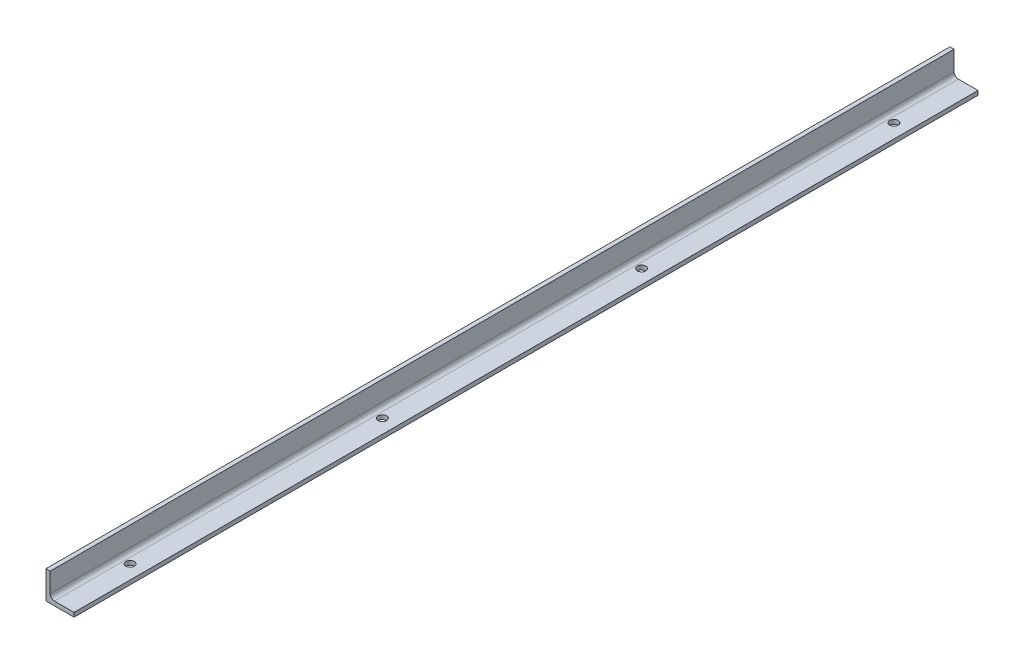
SolidWorks part; units mm, degrees
ref_plane "Plan de face" through (0, 0, 0) normal (0, 0, 1) x (1, 0, 0)
ref_plane "Plan de dessus" through (0, 0, 0) normal (0, 1, 0) x (1, 0, 0)
ref_plane "Plan de droite" through (0, 0, 0) normal (1, 0, 0) x (0, 0, -1)
sketch "Esquisse1" plane through (0, 0, 0) normal (0, 0, 1) x (1, 0, 0)
  line L0 (0, 0) -> (0, 20)
  line L1 (0, 20) -> (3, 20)
  line L2 (3, 20) -> (3, 6)
  line L3 (6, 3) -> (20, 3)
  line L4 (20, 3) -> (20, 0)
  line L5 (20, 0) -> (0, 0)
  arc A0 (3, 6) -> (6, 3) centre (6, 6) ccw
  dimension "D5" = 3
  dimension "D1" = 20
  dimension "D2" = 20
  dimension "D3" = 3
  dimension "D4" = 3
extrude "Boss.-Extru.1" add sketch "Esquisse1" along normal blind 645
sketch "Esquisse2" plane through (0, 0, 0) normal (0, -1, 0) x (-1, 0, 0)
  line L0 (0, 0) -> (-20, 0) construction
  line L1 (0, -645) -> (-20, -645) construction
  line L4 (0, -645) -> (0, 0) construction
  circle A0 centre (-10, -50) radius 3
  circle A1 centre (-10, -595) radius 3
  circle A2 centre (-10, -230) radius 3
  circle A3 centre (-10, -415) radius 3
  point P10 (-10, 0)
  dimension "D1" = 6
  dimension "D2" = 6
  dimension "D9" = 6
  dimension "D10" = 6
  dimension "D13" = 10
  dimension "D3" = 50
  dimension "D4" = 645
  dimension "D5" = 545
  dimension "D6" = 50
  dimension "D7" = 10
  dimension "D8" = 10
  dimension "D11" = 180
  dimension "D12" = 180
  dimension "D14" = 10
extrude "Enlèv. mat.-Extru.1" cut sketch "Esquisse2" against normal blind 955
